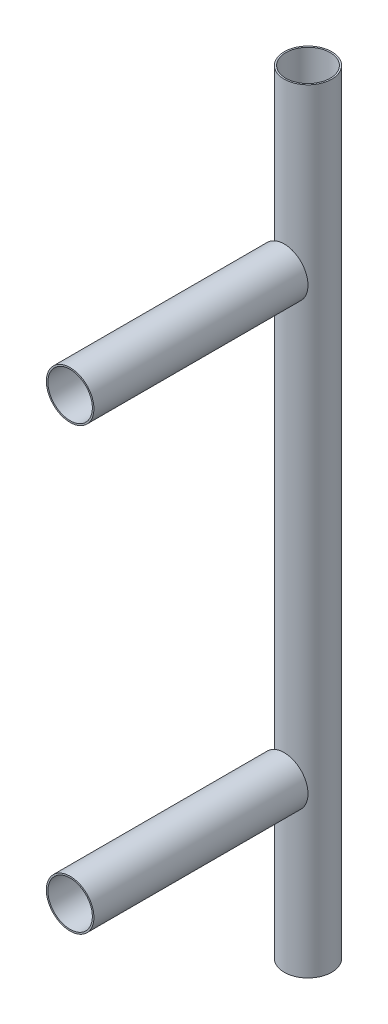
SolidWorks part; units mm, degrees
material "AISI 4130 Steel, annealed at 865C"
ref_plane "X-Y Datum" through (0, 0, 0) normal (0, 0, 1) x (1, 0, 0)
ref_plane "X-Z Datum" through (0, 0, 0) normal (0, 1, 0) x (1, 0, 0)
ref_plane "Y-Z Datum" through (0, 0, 0) normal (1, 0, 0) x (0, 0, -1)
sketch "Sketch1" plane through (0, 0, 0) normal (0, 1, 0) x (1, 0, 0)
  circle A0 centre (0, 0) radius 12.7
  circle A1 centre (0, 0) radius 11.8745
  dimension "D1" = 25.4
  dimension "D2" = 23.749
extrude "Boss-Extrude1" add sketch "Sketch1" along normal blind 413.004
ref_plane "Plane1" through (0, 0, 12.7) normal (0, 0, 1) x (1, 0, 0)
sketch "Sketch2" plane through (0, 0, 12.7) normal (0, 0, 1) x (1, 0, 0)
  line L0 (12.7, 0) -> (12.7, 413.004) construction
  line L1 (-12.7, 413.004) -> (-12.7, 0) construction
  line L2 (12.7, 0) -> (12.7, 413.004) construction
  line L3 (-12.7, 413.004) -> (-12.7, 0) construction
  line L5 (11.8745, 413.004) -> (-11.8745, 413.004) construction
  circle A0 centre (0, 324.104) radius 12.7
  circle A1 centre (0, 324.104) radius 11.8745
  circle A2 centre (0, 88.9) radius 12.7
  circle A3 centre (0, 88.9) radius 11.8745
  circle A4 centre (0, 206.502) radius 12.7 construction
  circle A5 centre (0, 206.502) radius 11.8745 construction
  dimension "D1" = 23.749
  dimension "D2" = 23.749
  dimension "D5" = 23.749
  dimension "D3" = 88.9
  dimension "D4" = 88.9
  dimension "D6" = 206.502
extrude "Boss-Extrude2" add sketch "Sketch2" along normal blind 114.3 separate body
